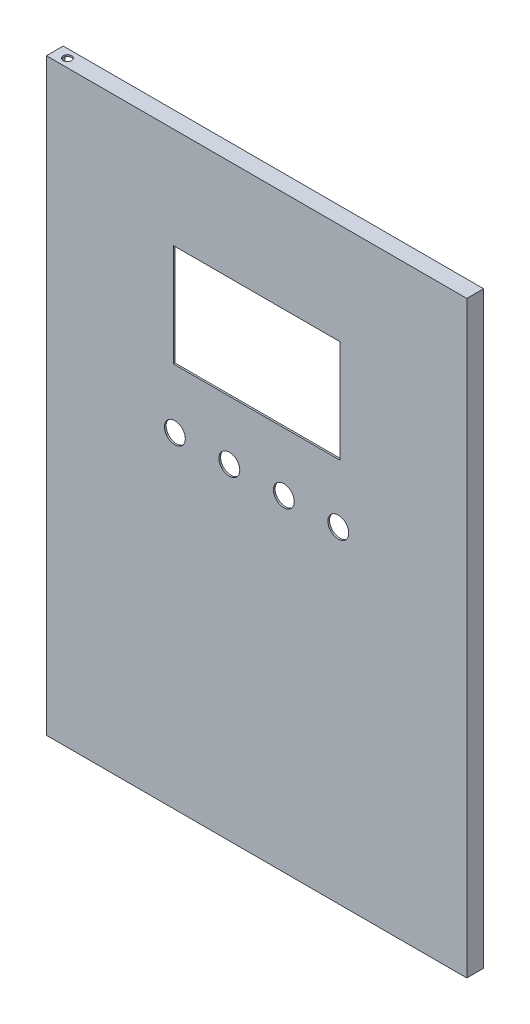
SolidWorks part; units mm, degrees
ref_plane "Front Plane" through (0, 0, 0) normal (0, 0, 1) x (1, 0, 0)
ref_plane "Top Plane" through (0, 0, 0) normal (0, 1, 0) x (1, 0, 0)
ref_plane "Right Plane" through (0, 0, 0) normal (1, 0, 0) x (0, 0, -1)
sketch "Sketch1" plane through (0, 0, 0) normal (0, 0, 1) x (1, 0, 0)
  line L1 (0, 0) -> (250, 0)
  line L2 (0, 0) -> (0, -350)
  line L3 (0, -350) -> (250, -350)
  line L4 (250, 0) -> (250, -350)
  dimension "D1" = 250
  dimension "D2" = 350
extrude "Boss-Extrude1" add sketch "Sketch1" along normal blind 10
sketch "Sketch2" plane through (0, 0, 0) normal (0, 0, -1) x (-1, 0, 0)
  line L0 (-249, -1) -> (-249, -349)
  line L1 (-249, -349) -> (-1, -349)
  line L2 (-1, -349) -> (-1, -1)
  line L3 (-1, -1) -> (-249, -1)
  line L4 (0, -350) -> (0, 0)
  line L5 (0, 0) -> (-250, 0)
  line L6 (-250, 0) -> (-250, -350)
  line L7 (-250, -350) -> (0, -350)
  line L8 (0, -350) -> (0, 0)
  line L9 (0, 0) -> (-250, 0)
  line L10 (-250, 0) -> (-250, -350)
  line L11 (-250, -350) -> (0, -350)
  dimension "D1" = 0
  dimension "D2" = 1
extrude "Cut-Extrude1" cut sketch "Sketch2" against normal blind 9 contours L0 L1 L2 L3
sketch "Sketch3" plane through (0, 0, 0) normal (0, 1, 0) x (1, 0, 0)
  line L0 (0, -5) -> (7.5, -5) construction
  line L1 (0, -10) -> (0, 0) construction
  circle A0 centre (7.5, -5) radius 2.5
  dimension "D2" = 5
  dimension "D1" = 7.5
extrude "Cut-Extrude2" cut sketch "Sketch3" against normal through all both and the other way through all
sketch "Sketch4" plane through (0, 0, 10) normal (0, 0, 1) x (1, 0, 0)
  line L1 (75.5, -60) -> (174.5, -60)
  line L2 (75.5, -60) -> (75.5, -121)
  line L3 (75.5, -121) -> (174.5, -121)
  line L4 (174.5, -60) -> (174.5, -121)
  line L6 (250, 0) -> (0, 0) construction
  line L7 (74, -58.5) -> (74, -122.5)
  line L8 (74, -122.5) -> (176, -122.5)
  line L9 (176, -58.5) -> (176, -122.5)
  line L10 (74, -58.5) -> (176, -58.5)
  line L11 (0, 0) -> (0, -350) construction
  line L12 (250, -350) -> (250, 0) construction
  dimension "D1" = 74
  dimension "D2" = 74
  dimension "D3" = 60
  dimension "D4" = 61
  dimension "D5" = 1.5
extrude "Cut-Extrude3" cut sketch "Sketch4" against normal blind 10 contours L2 L1 L4 L3
sketch "Sketch5" plane through (0, 0, 10) normal (0, 0, 1) x (1, 0, 0)
  line L0 (0, -156) -> (250, -156) construction
  line L1 (0, 0) -> (0, -350) construction
  line L2 (250, -350) -> (250, 0) construction
  line L3 (75.5, -121) -> (174.5, -121) construction
  line L4 (125, -156) -> (125, -167.0447) construction
  circle A0 centre (108.8, -156) radius 6.2
  circle A1 centre (141.2, -156) radius 6.2
  circle A2 centre (76.4, -156) radius 6.2
  circle A3 centre (173.6, -156) radius 6.2
  point P7 (226.8606, -156)
  point P9 (115, -156)
  point P10 (135, -156)
  point P11 (125, -156)
  point P16 (82.6, -156)
  point P17 (102.6, -156)
  dimension "D4" = 12.4
  dimension "D5" = 12.4
  dimension "D7" = 12.4
  dimension "D1" = 35
  dimension "D2" = 10
  dimension "D3" = 10
  dimension "D6" = 20
extrude "Cut-Extrude4" cut sketch "Sketch5" against normal up to next
